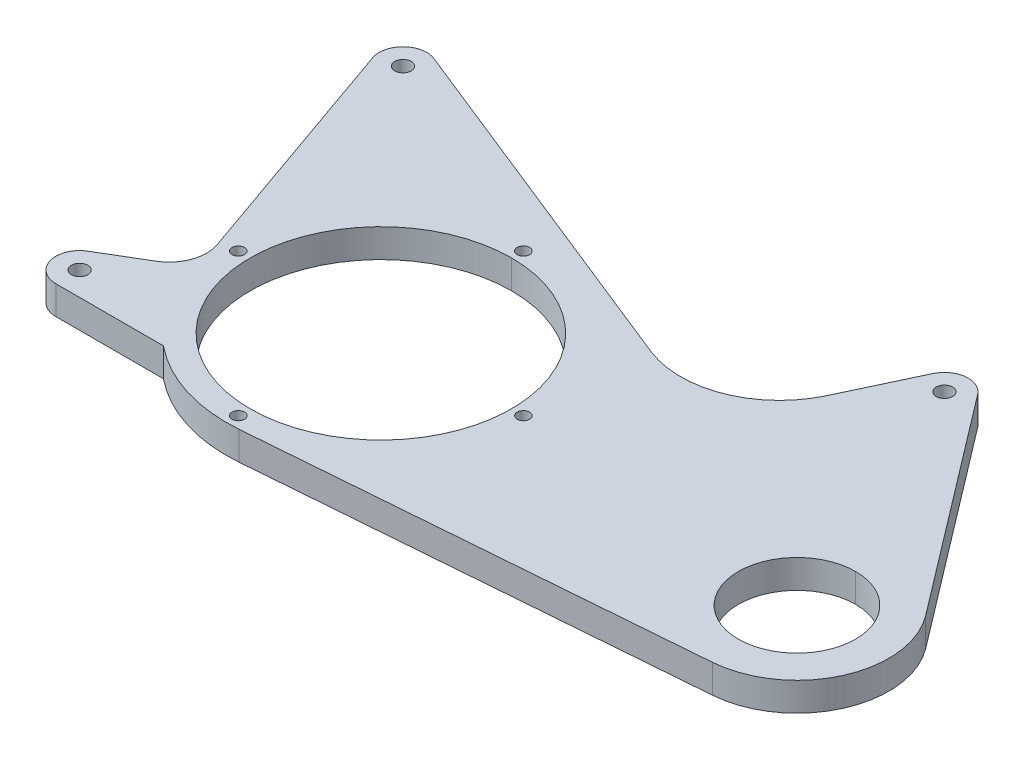
SolidWorks part; units mm, degrees
material "7075-T6 (SN)"
ref_plane "X-Y Datum" through (0, 0, 0) normal (0, 0, 1) x (1, 0, 0)
ref_plane "X-Z Datum" through (0, 0, 0) normal (0, 1, 0) x (1, 0, 0)
ref_plane "Y-Z Datum" through (0, 0, 0) normal (1, 0, 0) x (0, 0, -1)
sketch "Sketch1" plane through (0, 0, 0) normal (0, 1, 0) x (1, 0, 0)
  line L0 (-228.6, -165.1) -> (-123.19, -116.0015) construction
  line L1 (0, 0) -> (54.61, -127) construction
  line L2 (-123.19, -116.0015) -> (54.61, -127) construction
  line L3 (-228.6, -165.1) -> (-228.6, 0) construction
  line L4 (-116.84, 0) -> (0, 0) construction
  line L5 (-228.6, 0) -> (-116.84, 0) construction
  line L10 (-228.6, 0) -> (-123.19, -116.0015) construction
  line L11 (-123.19, -116.0015) -> (10.0337, -23.3342) construction
  line L13 (-205.5752, -163.9004) -> (-162.4182, -163.9004)
  line L15 (-207.9749, -9.9568) -> (-62.7807, -68.145)
  line L16 (-118.2737, -177.7185) -> (57.5346, -163.7137)
  line L17 (17.6135, -17.566) -> (83.9187, -104.6964)
  line L18 (1.4126, -19.2843) -> (-12.1766, -48.2122)
  line L20 (-210.4442, -146.1889) -> (-193.2968, -135.9903)
  line L21 (-220.5059, -21.9521) -> (-186.7823, -118.0534)
  circle A0 centre (-211.5182, -18.7982) radius 9.525 construction
  circle A2 centre (10.0337, -23.3342) radius 9.525 construction
  circle A3 centre (-211.5182, -18.7982) radius 3.3 construction
  circle A4 centre (-205.5752, -154.3754) radius 3.3 construction
  circle A5 centre (-123.19, -116.0015) radius 52.3875
  circle A6 centre (54.61, -127) radius 23.5
  circle A7 centre (0, 0) radius 12.7 construction
  circle A8 centre (-228.6, -165.1) radius 12.7 construction
  circle A9 centre (-228.6, 0) radius 12.7 construction
  circle A10 centre (10.0337, -23.3342) radius 3.3 construction
  circle A11 centre (-123.19, -173.1515) radius 2.5 construction
  circle A14 centre (-123.19, -116.0015) radius 61.9125 construction
  circle A15 centre (-123.19, -116.0015) radius 57.15 construction
  circle A17 centre (-205.5752, -154.3754) radius 9.525 construction
  circle A18 centre (54.61, -127) radius 36.83 construction
  circle A19 centre (-48.0406, -31.3647) radius 39.624 construction
  arc A20 (-12.1766, -48.2122) -> (-62.7807, -68.145) centre (-48.0406, -31.3647) cw
  arc A23 (-162.4182, -163.9004) -> (-118.2737, -177.7185) centre (-123.19, -116.0015) ccw
  arc A24 (57.5346, -163.7137) -> (83.9187, -104.6964) centre (54.61, -127) ccw
  arc A25 (1.4126, -19.2843) -> (17.6135, -17.566) centre (10.0337, -23.3342) cw
  circle A27 centre (-200.9981, -123.0419) radius 15.0656 construction
  arc A28 (-210.4442, -146.1889) -> (-205.5752, -163.9004) centre (-205.5752, -154.3754) ccw
  arc A29 (-193.2968, -135.9903) -> (-186.7823, -118.0534) centre (-200.9981, -123.0419) ccw
  arc A30 (-220.5059, -21.9521) -> (-207.9749, -9.9568) centre (-211.5182, -18.7982) cw
  point P36 (-123.19, -116.0015)
  dimension "D1" = 165.1
  dimension "D2" = 105.41
  dimension "D8" = 25.4
  dimension "D9" = 104.775
  dimension "D10" = 47
  dimension "D11" = 19.05
  dimension "D12" = 6.6
  dimension "D23" = 5
  dimension "D14" = 123.825
  dimension "D19" = 79.248
  dimension "D20" = 31.3647
  dimension "D16" = 73.66
  dimension "D25" = 31.3335
  dimension "D21" = 30.1312
  dimension "D3" = 111.76
  dimension "D4" = 228.6
  dimension "D5" = 127
  dimension "D6" = 49.0985
  dimension "D7" = 283.21
  dimension "D13" = 25.4
  dimension "D15" = 25.4
  dimension "D17" = 25.4
  dimension "D18" = 48.0406
  dimension "D22" = 4.5771
  dimension "D24" = 57.15
extrude "Boss-Extrude1" add sketch "Sketch1" along normal blind 11.43
hole_wizard "M6 Clearance Hole1" positions "Sketch2" profile "Sketch3" hole size "M6" standard "ANSI Metric" end condition through all
sketch "Sketch2" plane through (0, 0, 0) normal (0, -1, 0) x (-1, 0, 0)
  point P0 (-10.0337, -23.3342)
  point P3 (211.5182, -18.7982)
  point P6 (205.5752, -154.3754)
sketch "Sketch3" plane through (10.0337, 0, 23.3342) normal (1, 0, 0) x (0, 0, -1)
  line L0 (0, 0) -> (0, 11.43)
  line L1 (0, 11.43) -> (3.3, 11.43)
  line L2 (3.3, 11.43) -> (3.3, 0)
  line L5 (3.3, 0) -> (0, 0)
  line L11 (0, -6.35) -> (0, 107.95) construction
  dimension "Thru Hole Dia." = 6.6
  dimension "Thru Hole Depth" = 11.43
hole_wizard "Ø5.0mm Dowel Hole1" positions "Sketch4" profile "Sketch5" hole size "Ø5.0" standard "ANSI Metric" end condition through all
sketch "Sketch4" plane through (0, 0, 0) normal (0, -1, 0) x (-1, 0, 0)
  point P0 (123.19, -173.1515)
sketch "Sketch5" plane through (-123.19, 0, 173.1515) normal (1, 0, 0) x (0, 0, -1)
  line L0 (0, 0) -> (0, 11.43)
  line L1 (0, 11.43) -> (2.5, 11.43)
  line L2 (2.5, 11.43) -> (2.5, 0)
  line L5 (2.5, 0) -> (0, 0)
  line L11 (0, -6.35) -> (0, 107.95) construction
  dimension "Thru Hole Dia." = 5
  dimension "Thru Hole Depth" = 11.43
pattern_circular "CirPattern1" count 4 over 360 about axis through (-123.19, 0, 116.0015) along (0, 1, 0) of "Ø5.0mm Dowel Hole1"
ref_point "Point1"
ref_point "Point2"
ref_plane "Plane1" through (-123.19, 0, 0) normal (1, 0, 0) x (0, 0, -1)
ref_plane "Plane2" through (54.61, 0, 0) normal (1, 0, 0) x (0, 0, -1)
split line "Split Line1"
split line "Split Line2"
